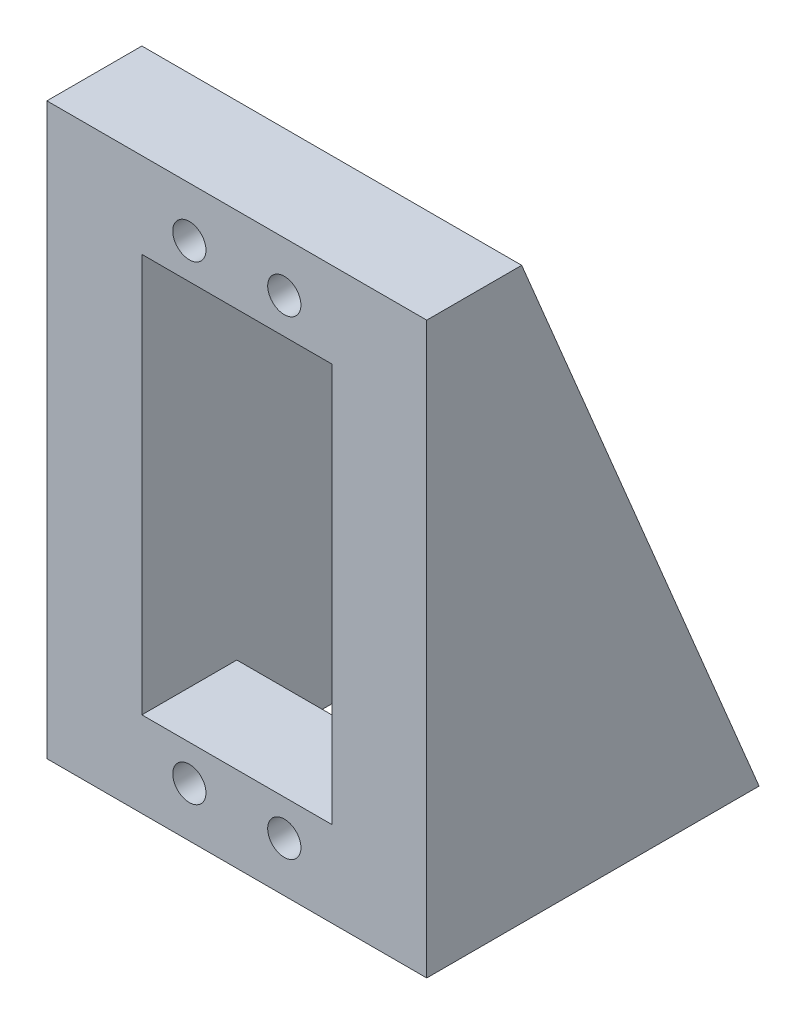
SolidWorks part; units mm, degrees
ref_plane "Front" through (0, 0, 0) normal (0, 0, 1) x (1, 0, 0)
ref_plane "Top" through (0, 0, 0) normal (0, 1, 0) x (1, 0, 0)
ref_plane "Right" through (0, 0, 0) normal (1, 0, 0) x (0, 0, -1)
sketch "Sketch2" plane through (0, 0, 0) normal (0, 0, 1) x (1, 0, 0)
  line L0 (0, 24.75) -> (0, -24.75)
  line L1 (-20, -30) -> (20, -30)
  line L2 (-20, -30) -> (-20, 30)
  line L3 (-20, 30) -> (20, 30)
  line L4 (20, -30) -> (20, 30)
  line L5 (-5, -24.75) -> (5, -24.75)
  line L6 (-5, 24.75) -> (5, 24.75)
  line L7 (-11, 21) -> (11, 21)
  line L8 (-11, 21) -> (-11, -21)
  line L9 (-11, -21) -> (11, -21)
  line L10 (11, 21) -> (11, -21)
  line L11 (-11, 21) -> (11, -21) construction
  line L12 (-11, -21) -> (11, 21) construction
  circle A0 centre (-5, 24.75) radius 1.75
  circle A1 centre (5, 24.75) radius 1.75
  circle A2 centre (-5, -24.75) radius 1.75
  circle A3 centre (5, -24.75) radius 1.75
  point P0 (0, 0)
  point P6 (0, 0)
  point P14 (0, 0)
  point P17 (0, -24.75)
  point P20 (0, 24.75)
  dimension "D1" = 42
  dimension "D2" = 22
  dimension "D3" = 40
  dimension "D4" = 60
  dimension "D5" = 9
  dimension "D6" = 9
  dimension "D7" = 49.5
  dimension "D8" = 10
  dimension "D9" = 0
extrude "Boss-Extrude1" add sketch "Sketch2" along normal blind 10
sketch "Sketch3" plane through (-20, 0, 0) normal (-1, 0, 0) x (0, 0, 1)
  line L0 (10, 30) -> (10, -30)
  line L1 (10, -30) -> (25, -30)
  line L2 (25, -30) -> (10, 30)
  dimension "D1" = 15
extrude "Boss-Extrude2" [suppressed] add sketch "Sketch3" against normal blind 10
sketch "Sketch4" plane through (20, 0, 0) normal (1, 0, 0) x (0, 0, -1)
  line L0 (0, -30) -> (25, -30)
  line L1 (25, -30) -> (0, 30)
  line L6 (0, -30) -> (0, 30)
  line L7 (0, 30) -> (-10, 30)
  line L8 (-10, 30) -> (-10, -30)
  line L9 (-10, -30) -> (0, -30)
  line L11 (0, 30) -> (-10, 30)
  line L13 (-10, -30) -> (0, -30)
  line L15 (-10, 30) -> (-10, -30)
  dimension "D1" = 25
  dimension "D2" = 0
extrude "Boss-Extrude3" add sketch "Sketch4" against normal blind 10
pattern_linear "LPattern1" [suppressed] count 2 spacing 30
pattern_linear "LPattern2" count 2 spacing 30 along (-1, 0, 0) of "Boss-Extrude3"
sketch "Sketch5" plane through (0, -30, 0) normal (0, -1, 0) x (1, 0, 0)
  line L0 (-16, -25) -> (-16, -16.7434)
  line L1 (-20, -25) -> (-10, -25) construction
  line L2 (-16, -16.7434) -> (-16, -6.7434)
  line L3 (-16, -6.7434) -> (-16, 3.2566)
  line L4 (-20, 10) -> (-20, -25) construction
  line L5 (0, 10) -> (0, 0)
  line L6 (-20, 10) -> (20, 10) construction
  line L7 (-10, 0) -> (10, 0) construction
  circle A0 centre (-16, -16.7434) radius 1.25
  circle A1 centre (-16, 3.2566) radius 1.25
  circle A2 centre (-16, -6.7434) radius 1.25
  circle A3 centre (16, -16.7434) radius 1.25
  circle A4 centre (16, -6.7434) radius 1.25
  circle A5 centre (16, 3.2566) radius 1.25
  dimension "D2" = 10
  dimension "D4" = 4
  dimension "D1" = 8.2566
  dimension "D3" = 10
extrude "Cut-Extrude1" cut sketch "Sketch5" against normal blind 12 contours A1 | A2 | A0 | A5 | A4 | A3
